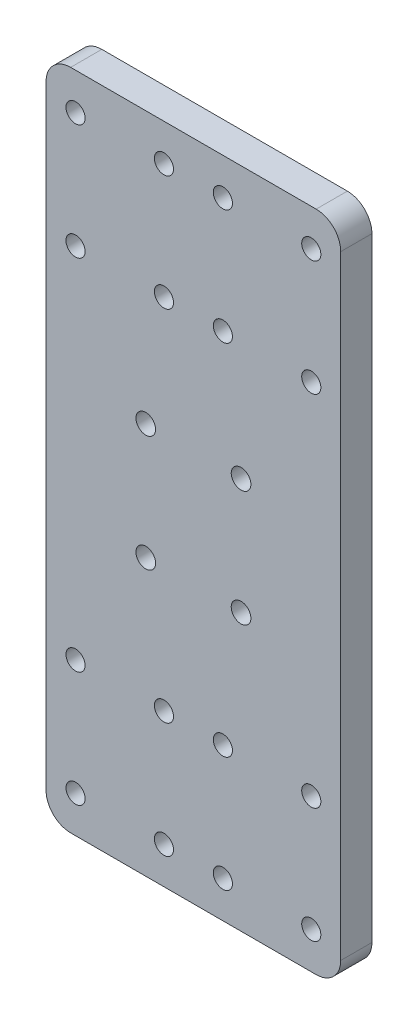
SolidWorks part; units mm, degrees
ref_plane "Front Plane" through (0, 0, 0) normal (0, 0, 1) x (1, 0, 0)
ref_plane "Top Plane" through (0, 0, 0) normal (0, 1, 0) x (1, 0, 0)
ref_plane "Right Plane" through (0, 0, 0) normal (1, 0, 0) x (0, 0, -1)
sketch "Sketch1" plane through (0, 0, 0) normal (0, 0, 1) x (1, 0, 0)
  line L0 (0, 0) -> (68.5241, 0) construction
  line L1 (-25, -67.5) -> (25, -67.5)
  line L2 (-30, -62.5) -> (-30, 62.5)
  line L3 (-25, 67.5) -> (25, 67.5)
  line L4 (30, -62.5) -> (30, 62.5)
  line L5 (-30, -67.5) -> (30, 67.5) construction
  line L6 (-30, 67.5) -> (30, -67.5) construction
  line L7 (0, 0) -> (0, 39.7219) construction
  circle A0 centre (24, 60) radius 1.95
  circle A1 centre (6, 60) radius 1.95
  circle A2 centre (6, 36.5) radius 1.95
  circle A3 centre (24, 36.5) radius 1.95
  arc A4 (-25, -67.5) -> (-30, -62.5) centre (-25, -62.5) cw
  arc A5 (25, -67.5) -> (30, -62.5) centre (25, -62.5) ccw
  arc A6 (25, 67.5) -> (30, 62.5) centre (25, 62.5) cw
  arc A7 (-30, 62.5) -> (-25, 67.5) centre (-25, 62.5) cw
  circle A8 centre (-6, 60) radius 1.95
  circle A9 centre (-24, 60) radius 1.95
  circle A10 centre (-24, 36.5) radius 1.95
  circle A11 centre (-6, 36.5) radius 1.95
  circle A12 centre (-24, -36.5) radius 1.95
  circle A13 centre (-6, -36.5) radius 1.95
  circle A14 centre (6, -36.5) radius 1.95
  circle A15 centre (24, -36.5) radius 1.95
  circle A16 centre (24, -60) radius 1.95
  circle A17 centre (6, -60) radius 1.95
  circle A18 centre (-6, -60) radius 1.95
  circle A19 centre (-24, -60) radius 1.95
  circle A20 centre (9.7, -11.3) radius 2
  circle A21 centre (9.7, 12.3) radius 2
  circle A22 centre (-9.7, -11.3) radius 2
  circle A23 centre (-9.7, 12.3) radius 2
  point P0 (0, 0)
  point P20 (0, 0)
  point P25 (34.262, 0)
  dimension "D4" = 3.9
  dimension "D8" = 5
  dimension "D10" = 4
  dimension "D13" = 4
  dimension "D1" = 135
  dimension "D2" = 60
  dimension "D3" = 23.5
  dimension "D5" = 18
  dimension "D6" = 6
  dimension "D7" = 36.5
  dimension "D9" = 48.7
  dimension "D11" = 9.7
  dimension "D12" = 23.6
extrude "Boss-Extrude1" add sketch "Sketch1" along normal blind 6.35
